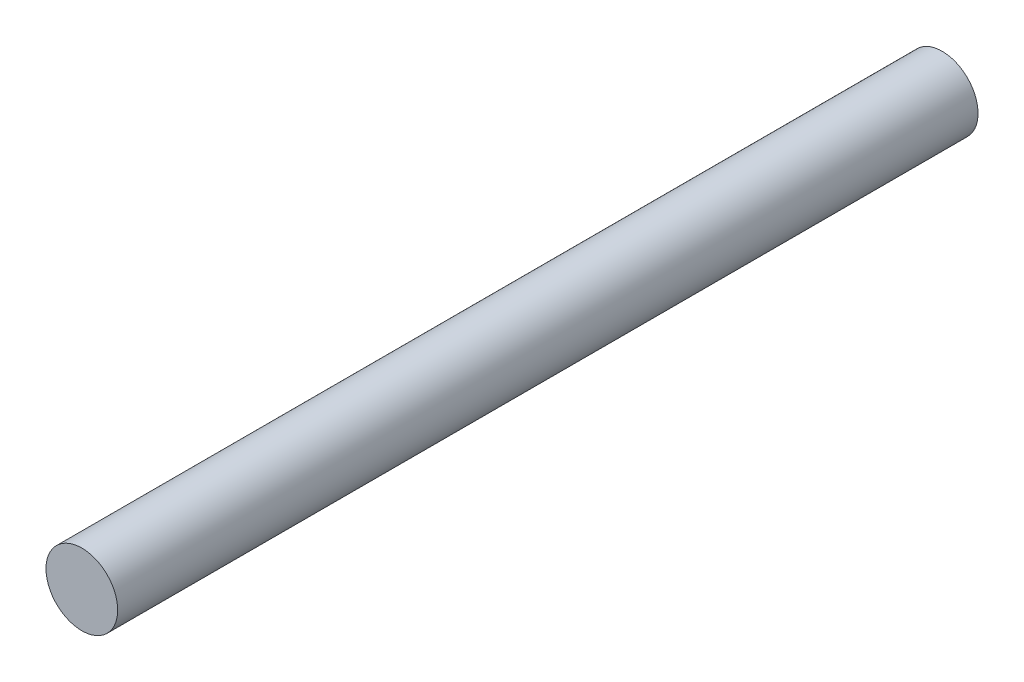
SolidWorks part; units mm, degrees
material "Hexcel AS4C (3000 Filaments)"
ref_plane "Front" through (0, 0, 0) normal (0, 0, 1) x (1, 0, 0)
ref_plane "Top" through (0, 0, 0) normal (0, 1, 0) x (1, 0, 0)
ref_plane "Right" through (0, 0, 0) normal (1, 0, 0) x (0, 0, -1)
sketch "Sketch1" plane through (0, 0, 0) normal (0, 0, 1) x (1, 0, 0)
  circle A0 centre (0, 0) radius 3.175
extrude "Boss-Extrude1" add sketch "Sketch1" along normal blind 76.2
equation "\"truss_member_od\" = .25in"
equation "\"truss_member_id\"= 0in"
equation "\"truss_member_L1\" = 2.125in"
equation "\"D1@Sketch1\"=\"truss_member_od\""
equation "\"D1@Boss-Extrude1\"=\"truss_member_L2\""
equation "\"truss_member_L2\" = 3in"
equation "\"connector_hole_depth\" = .375in"
